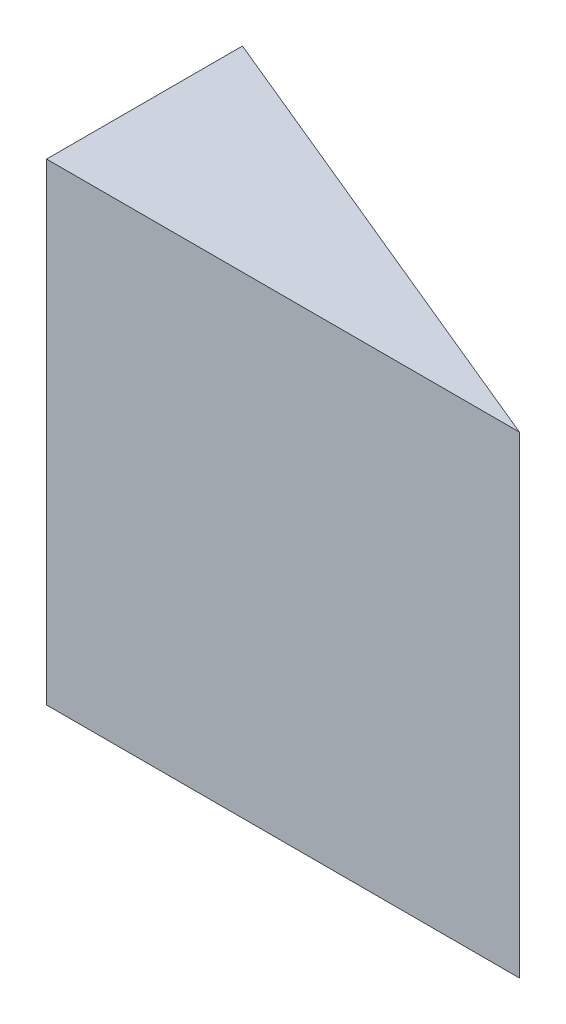
SolidWorks part; units mm, degrees
material "6061 Alloy"
ref_plane "Front Plane" through (0, 0, 0) normal (0, 0, 1) x (1, 0, 0)
ref_plane "Top Plane" through (0, 0, 0) normal (0, 1, 0) x (1, 0, 0)
ref_plane "Right Plane" through (0, 0, 0) normal (1, 0, 0) x (0, 0, -1)
sketch "Sketch1" plane through (0, 0, 0) normal (0, 1, 0) x (1, 0, 0)
  line L0 (12.7, -13.0829) -> (-12.7, -2.5619)
  line L5 (-12.7, -13.0829) -> (12.7, -13.0829)
  line L6 (-12.7, -13.0829) -> (-12.7, -2.5619)
  point P0 (0, 0)
  point P1 (0, 0)
  dimension "D1" = 25.4
  dimension "D2" = 22.5
extrude "Boss-Extrude1" add sketch "Sketch1" along normal mid plane 25.4
